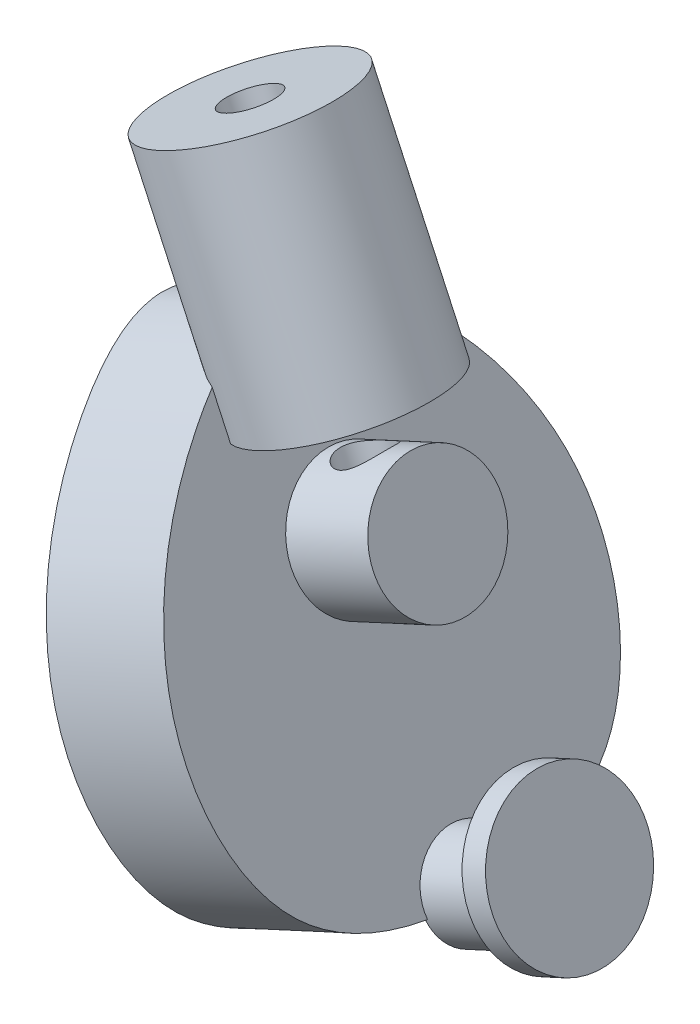
SolidWorks part; units mm, degrees
material "Aleación 6061"
ref_plane "Alzado" through (0, 0, 0) normal (0, 0, 1) x (1, 0, 0)
ref_plane "Planta" through (0, 0, 0) normal (0, 1, 0) x (1, 0, 0)
ref_plane "Vista lateral" through (0, 0, 0) normal (1, 0, 0) x (0, 0, -1)
sketch3d "Sk_puntos_Plano_placa"
  point P0 (433.1318, 388.4762, 0)
  point P1 (449.8942, 352.1579, 0)
  point P2 (433.1318, 388.4762, 40)
ref_plane "Plano_placa" through (504.8801, 233.0216, 0) normal (-0.908, -0.4191, 0) x (0, 0, 1)
sketch "Sk_Placa" plane through (504.8801, 233.0216, 0) normal (-0.908, -0.4191, 0) x (0, 0, 1)
  spline S0 degree 3 poles (-5.9029, 222.2845) (0, 226.1278) (5.9029, 222.2845) (9.0721, 215.8434) (6.4788, 208.2172) (0, 206.671) (-6.4788, 208.2172) (-9.0721, 215.8434) (-5.9029, 222.2845) (0, 226.1278) (5.9029, 222.2845) knots -0.378517 -0.275079 -0.085901 0 0.085901 0.275079 0.378517 0.5 0.621483 0.724921 0.914099 1 1.085901 1.275079 1.378517 only from (0, 225.2132) to (0, 225.2132)
extrude "Placa" add sketch "Sk_Placa" along normal mid plane 5
sketch3d "Sk_Buje_cable"
  line L0 (411.6202, 444.63, 0) -> (415.3917, 436.4584, 0)
  dimension "D1" = 9
sweep "Buje_cable" add path "Sk_Buje_cable" circular profile diameter 7 parameters "D3"=7
sketch3d "Sk_Tornillo_pisacables"
  line L0 (409.8043, 429.4741, 0) -> (418.8839, 433.6647, 0)
  dimension "D1" = 10
sweep "Tornillo_pisacables" add path "Sk_Tornillo_pisacables" circular profile diameter 5 parameters "D3"=5
sketch3d "Sk_Paso_cable_principal"
  line L0 (410.7821, 446.4459, 0) -> (418.3251, 430.1027, 0)
  dimension "D1" = 18
sweep "Paso_cable_principal" cut path "Sk_Paso_cable_principal" circular profile diameter 2 parameters "D3"=2
sketch3d "Sk_Pestana"
  line L0 (420.0572, 422.5317, 0) -> (423.3259, 424.0403, 0)
  dimension "D1" = 3.6
sweep "Pestana" add path "Sk_Pestana" circular profile diameter 3.6 parameters "D3"=3.6
sketch3d "Sk_Labio"
  line L0 (423.0744, 424.5851, 0) -> (423.9824, 425.0041, 0)
  dimension "D1" = 1
sweep "Labio" add path "Sk_Labio" circular profile diameter 6 parameters "D3"=6
sketch3d "Sk_puntos_Plano_yugo"
  point P0 (436.7637, 390.1525, 0)
  point P1 (453.526, 353.8341, 0)
  point P2 (436.7637, 390.1525, 40)
ref_plane "Plano_yugo" through (508.512, 234.6978, 0) normal (-0.908, -0.4191, 0) x (0, 0, 1)
sketch3d "Sk_puntos_Plano_tiro"
  point P0 (420.0013, 426.4708, 0)
  point P1 (456.3197, 443.2332, 0)
  point P2 (420.0013, 426.4708, 40)
ref_plane "Plano_tiro" through (-88.5106, 191.773, 0) normal (0.4191, -0.908, 0) x (-0.908, -0.4191, 0)
